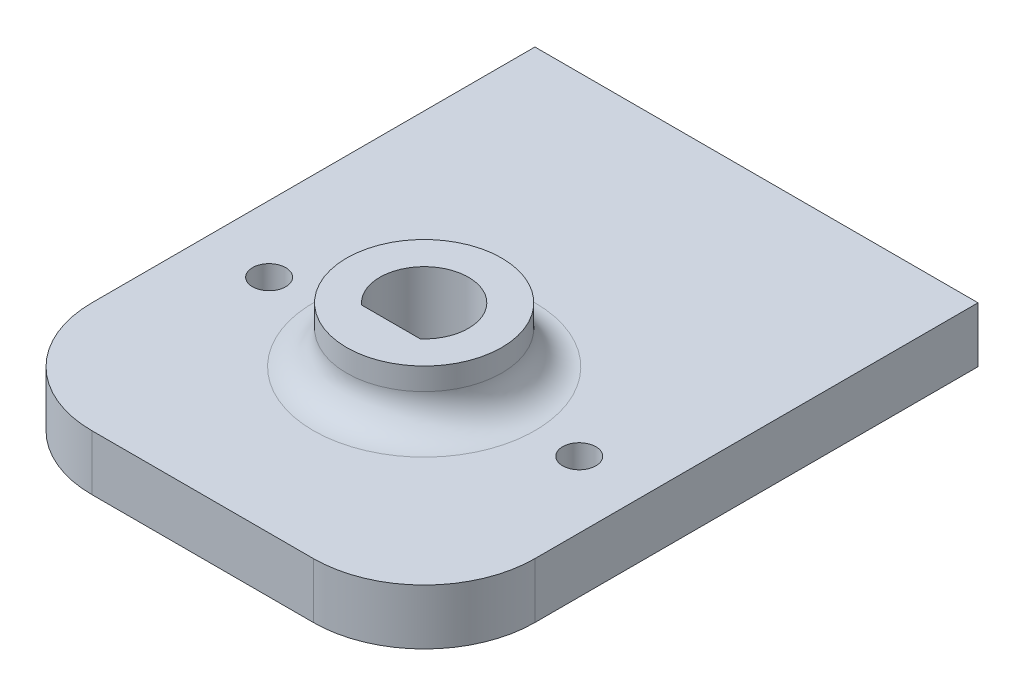
SolidWorks part; units mm, degrees
ref_plane "Front Plane" through (0, 0, 0) normal (0, 0, 1) x (1, 0, 0)
ref_plane "Top Plane" through (0, 0, 0) normal (0, 1, 0) x (1, 0, 0)
ref_plane "Right Plane" through (0, 0, 0) normal (1, 0, 0) x (0, 0, -1)
sketch "Sketch1" plane through (0, 0, 0) normal (0, 1, 0) x (1, 0, 0)
  line L0 (-20, 0) -> (20, 0) construction
  line L2 (-20, 20) -> (-20, -20)
  line L3 (-20, -20) -> (20, -20)
  line L4 (20, 20) -> (20, -20)
  line L5 (-20, 20) -> (20, -20) construction
  line L6 (-20, -20) -> (20, 20) construction
  line L7 (0, -4) -> (0, -3) construction
  line L8 (-2.6458, -3) -> (2.6458, -3)
  line L11 (-20, 20) -> (-20, 30)
  line L12 (-20, 30) -> (20, 30)
  line L13 (20, 20) -> (20, 30)
  circle A0 centre (14, 0) radius 1.5
  circle A1 centre (-14, 0) radius 1.5
  circle A2 centre (0, 0) radius 4 construction
  arc A3 (-2.6458, -3) -> (2.6458, -3) centre (0, 0) cw
  point P0 (0, 0)
  point P9 (0, 0)
  point P20 (0, -3)
  dimension "D1" = 3
  dimension "D2" = 3
  dimension "D3" = 6
  dimension "D4" = 6
  dimension "D8" = 8
  dimension "D5" = 40
  dimension "D6" = 40
  dimension "D7" = 1
  dimension "D9" = 50
extrude "Boss-Extrude1" add sketch "Sketch1" along normal blind 5
sketch "Sketch2" plane through (0, 5, 0) normal (0, 1, 0) x (1, 0, 0)
  line L0 (0, -4) -> (0, -3) construction
  line L1 (-2.6458, -3) -> (2.6458, -3) construction
  line L2 (-2.6458, -3) -> (2.6458, -3) construction
  circle A0 centre (0, 0) radius 4 construction
  circle A1 centre (0, 0) radius 7
  arc A2 (-2.6458, -3) -> (2.6458, -3) centre (0, 0) cw
  point P12 (0, -3)
  line M11 (2.6458, -3) -> (-2.6458, -3)
  arc M12 (-2.6458, -3) -> (2.6458, -3) centre (0, 0) cw
  dimension "D1" = 8
  dimension "D2" = 14
extrude "Boss-Extrude2" add sketch "Sketch2" along normal blind 5 contours A1 M12 M11
fillet "Fillet1" radius 10 2 edges at (20, 2.5, 20) (-20, 2.5, 20)
fillet "Fillet2" radius 3 1 edges at (0, 5, 7)
